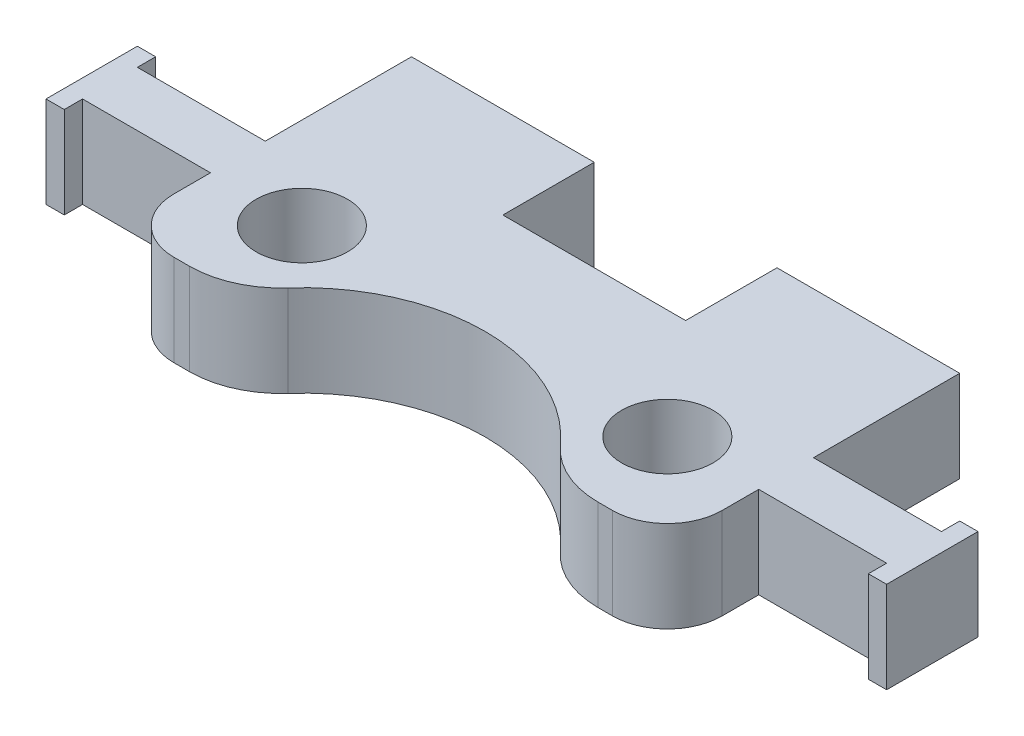
SolidWorks part; units mm, degrees
ref_plane "前视基准面" through (0, 0, 0) normal (0, 0, 1) x (1, 0, 0)
ref_plane "上视基准面" through (0, 0, 0) normal (0, 1, 0) x (1, 0, 0)
ref_plane "右视基准面" through (0, 0, 0) normal (1, 0, 0) x (0, 0, -1)
sketch "草图1" plane through (0, 0, 0) normal (0, 1, 0) x (1, 0, 0)
  line L0 (20, 21) -> (30, 21)
  line L1 (26.2064, 5) -> (27, 5)
  line L2 (0, 8) -> (0, 10)
  line L3 (0, 21) -> (10, 21)
  line L4 (30, 8) -> (30, 10)
  line L5 (-6.8407, 10) -> (38.4185, 10) construction
  line L6 (10, 21) -> (10, 16)
  line L7 (10, 16) -> (20, 16)
  line L8 (20, 21) -> (20, 16)
  line L9 (5, 23.3348) -> (5, 5) construction
  line L10 (25, 23.3348) -> (25, 5) construction
  line L11 (30, 10) -> (37, 10)
  line L12 (3, 5) -> (3.8457, 5)
  line L13 (37, 10) -> (37, 9)
  line L14 (37, 9) -> (38, 9)
  line L15 (38, 9) -> (38, 14)
  line L16 (38, 14) -> (37, 14)
  line L17 (37, 14) -> (37, 13)
  line L18 (37, 13) -> (30, 13)
  line L19 (0, 10) -> (-7, 10)
  line L20 (-7, 10) -> (-7, 9)
  line L21 (-7, 9) -> (-8, 9)
  line L22 (-8, 9) -> (-8, 14)
  line L23 (-8, 14) -> (-7, 14)
  line L24 (-7, 14) -> (-7, 13)
  line L25 (-7, 13) -> (0, 13)
  line L26 (0, 13) -> (0, 21)
  line L27 (30, 13) -> (30, 21)
  circle A0 centre (5, 10) radius 2.5
  circle A1 centre (25, 10) radius 2.5
  arc A2 (27, 5) -> (30, 8) centre (27, 8) ccw
  arc A3 (3, 5) -> (0, 8) centre (3, 8) cw
  arc A4 (22.4796, 6.6667) -> (7.5725, 6.6667) centre (15.026, 0) ccw
  arc A5 (26.2064, 5) -> (22.4796, 6.6667) centre (26.2064, 10) cw
  arc A6 (3.8457, 5) -> (7.5725, 6.6667) centre (3.8457, 10) ccw
  point P24 (25, 0)
  point P27 (5, 0)
  dimension "D9" = 5
  dimension "D1" = 3
  dimension "D2" = 5
  dimension "D3" = 5
  dimension "D4" = 10
  dimension "D5" = 10
  dimension "D6" = 6
  dimension "D7" = 5
  dimension "D8" = 5
  dimension "D10" = 7
  dimension "D11" = 7
  dimension "D12" = 7
  dimension "D13" = 7
  dimension "D14" = 8
extrude "凸台-拉伸1" add sketch "草图1" along normal blind 5
